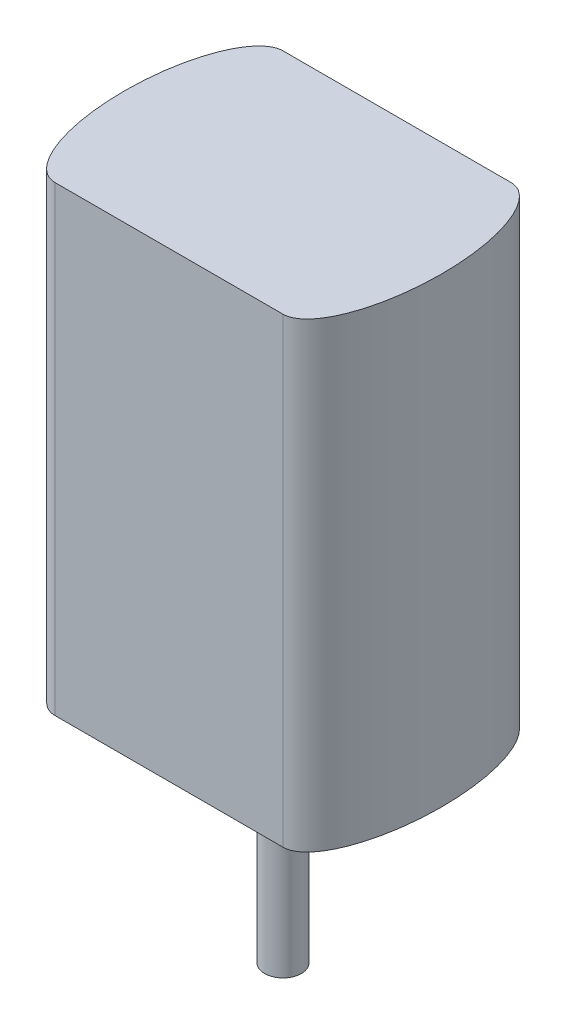
SolidWorks part; units mm, degrees
ref_plane "Front Plane" through (0, 0, 0) normal (0, 0, 1) x (1, 0, 0)
ref_plane "Top Plane" through (0, 0, 0) normal (0, 1, 0) x (1, 0, 0)
ref_plane "Right Plane" through (0, 0, 0) normal (1, 0, 0) x (0, 0, -1)
sketch "Sketch2" plane through (0, 0, 0) normal (0, 1, 0) x (1, 0, 0)
  line L0 (-6.2, 0) -> (6.2, 0)
  line L1 (-6.2, 6.2) -> (-6.2, -6.2)
  line L2 (6.2, 6.2) -> (6.2, -6.2)
  line L3 (6.2, -6.2) -> (-6.2, -6.2)
  line L4 (-6.2, 6.2) -> (6.2, 6.2)
  ellipse E0 centre (-6.2, 0) end of major axis (-6.2, -6.2) minor radius 2.429
  ellipse E1 centre (6.2, 0) end of major axis (6.2, -6.2) minor radius 2.4172
  point P4 (0, 0)
  point P7 (-6.2, 0)
  point P10 (6.2, 0)
extrude "Boss-Extrude1" add sketch "Sketch2" along normal blind 25.1 contours E1 L0 E0 L3 | E1 L4 E0 L0 | L2 E1 | L2 E1 L0 | L0 E1 L2
sketch "Sketch3" plane through (0, 0, 0) normal (0, -1, 0) x (1, 0, 0)
  circle A0 centre (0, 0) radius 3.075
extrude "Boss-Extrude2" add sketch "Sketch3" along normal blind 1.6
sketch "Sketch4" plane through (0, -1.6, 0) normal (0, -1, 0) x (1, 0, 0)
  circle A0 centre (0, 0) radius 1
extrude "Boss-Extrude3" add sketch "Sketch4" along normal blind 10.05
